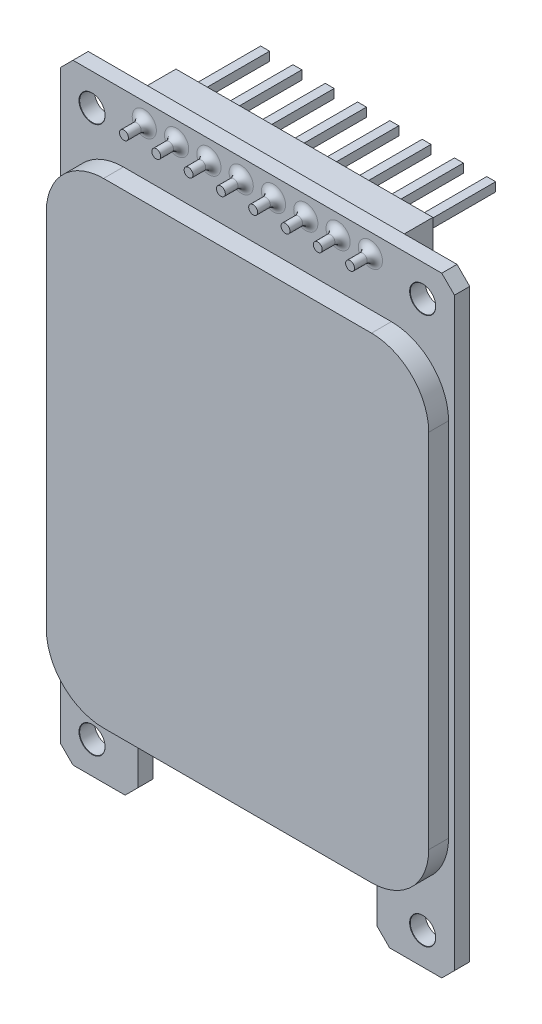
SolidWorks part; units mm, degrees
ref_plane "Ebene vorne" through (0, 0, 0) normal (1, 0, 0) x (0, 1, 0)
ref_plane "Ebene oben" through (0, 0, 0) normal (0, 0, 1) x (0, 1, 0)
ref_plane "Ebene rechts" through (0, 0, 0) normal (0, 1, 0) x (-1, 0, 0)
sketch "Skizze1" plane through (0, 0, 0) normal (0, 0, 1) x (0, 1, 0)
  line L0 (-24, 9.4) -> (-18.5, 9.4)
  line L1 (-24, -15.5) -> (24, -15.5)
  line L2 (-24, -15.5) -> (-24, -9.4)
  line L3 (-24, 15.5) -> (24, 15.5)
  line L4 (24, -15.5) -> (24, 15.5)
  line L5 (-24, -15.5) -> (24, 15.5) construction
  line L6 (-24, 15.5) -> (24, -15.5) construction
  line L7 (-18.5, 9.4) -> (-18.5, -9.4)
  line L8 (-18.5, -9.4) -> (-24, -9.4)
  line L9 (-24, 9.4) -> (-24, 15.5)
  point P0 (0, 0)
  point P8 (-18.5, 0)
  dimension "D1" = 48
  dimension "D2" = 31
  dimension "D3" = 5.5
  dimension "D4" = 6.1
extrude "Aufsatz-Linear austragen1" add sketch "Skizze1" along normal blind 1.2
chamfer "Fase1" distance 1 angle 45 6 edges at (-9.4, -24, 0.6) (9.4, -24, 0.6) (-15.5, -24, 0.6) (-15.5, 24, 0.6) (15.5, -24, 0.6) (15.5, 24, 0.6)
hole_wizard "Ø2.0 (2) Durchmesser Bohrung1" positions "Skizze2" profile "Skizze3" hole size "Ø2.0" standard "DIN" end condition up to next
sketch "Skizze2" plane through (0, 0, 1.2) normal (0, 0, 1) x (0, -1, 0)
  line L7 (-21.5, 13) -> (21.5, 13) construction
  line L8 (-21.5, 13) -> (-21.5, -13) construction
  line L9 (-21.5, -13) -> (21.5, -13) construction
  line L10 (21.5, -13) -> (21.5, 13) construction
  line L12 (-21.5, 0) -> (0, 0) construction
  line L14 (0, 0) -> (0, 13) construction
  point P2 (21.5, 13)
  point P4 (-21.5, 13)
  point P36 (21.5, -13)
  point P38 (-21.5, -13)
  dimension "D1" = 26
  dimension "D2" = 43
sketch "Skizze3" plane through (13, -21.5, 1.2) normal (1, 0, 0) x (0, -1, 0)
  line L0 (0, 0) -> (0, 1.2)
  line L1 (0, 1.2) -> (1, 1.2)
  line L2 (1, 1.2) -> (1, 0.025)
  line L3 (1, 0.025) -> (1.025, 0)
  line L5 (1.025, 0) -> (0, 0)
  line L6 (-1, 0.025) -> (-1.025, 0) construction
  line L11 (0, -6.35) -> (0, 107.95) construction
  dimension "Bohrerdurchmesser" = 2
  dimension "Bohrungstiefe" = 1.2
  dimension "Senkdurchmesser2 (Oben)" = 2.05
  dimension "Senkwinkel2 (Oben)" = 90
sketch "Skizze4" plane through (0, 0, 1.2) normal (0, 0, 1) x (1, 0, 0)
  line L1 (10.535, -18.715) -> (-10.535, -18.715)
  line L2 (15.035, -14.215) -> (15.035, 14.215)
  line L3 (10.535, 18.715) -> (-10.535, 18.715)
  line L4 (-15.035, -14.215) -> (-15.035, 14.215)
  line L5 (13.717, -17.397) -> (-13.717, 17.397) construction
  line L6 (13.717, 17.397) -> (-13.717, -17.397) construction
  arc A0 (-10.535, 18.715) -> (-15.035, 14.215) centre (-10.535, 14.215) ccw
  arc A1 (15.035, 14.215) -> (10.535, 18.715) centre (10.535, 14.215) ccw
  arc A2 (-15.035, -14.215) -> (-10.535, -18.715) centre (-10.535, -14.215) ccw
  arc A3 (10.535, -18.715) -> (15.035, -14.215) centre (10.535, -14.215) ccw
  point P0 (0, 0)
  point P7 (13.717, 17.397)
  point P25 (-13.717, 17.397)
  point P27 (-13.717, -17.397)
  point P29 (13.717, -17.397)
  dimension "D1" = 4.5
  dimension "D2" = 30.07
  dimension "D3" = 37.43
extrude "Aufsatz-Linear austragen2" add sketch "Skizze4" along normal blind 1.56
sketch "Skizze5" plane through (0, 0, 1.2) normal (0, 0, 1) x (1, 0, 0)
  line L0 (-15.5, 23) -> (-15.5, -23) construction
  line L1 (14.5, 24) -> (-14.5, 24) construction
  line L2 (-8.89, 22.5) -> (-6.35, 22.5) construction
  circle A0 centre (-8.89, 22.5) radius 0.35
  circle A1 centre (-6.35, 22.5) radius 0.35
  circle A2 centre (-3.81, 22.5) radius 0.35
  circle A3 centre (-1.27, 22.5) radius 0.35
  circle A4 centre (1.27, 22.5) radius 0.35
  circle A5 centre (3.81, 22.5) radius 0.35
  circle A6 centre (6.35, 22.5) radius 0.35
  circle A7 centre (8.89, 22.5) radius 0.35
  dimension "D1" = 0.7
  dimension "D2" = 6.61
  dimension "D3" = 1.5
  dimension "D5" = 2.54
  dimension "D4" = 8
extrude "Aufsatz-Linear austragen3" add sketch "Skizze5" along normal blind 1.6 and the other way blind 9.7
fillet "Verrundung1" radius 0.6 8 edges at (8.54, 22.5, 1.2) (6, 22.5, 1.2) (3.46, 22.5, 1.2) (0.92, 22.5, 1.2) (-4.16, 22.5, 1.2) (-6.7, 22.5, 1.2) (-9.24, 22.5, 1.2) (-1.62, 22.5, 1.2)
sketch "Skizze6" plane through (0, 0, 0) normal (0, 0, -1) x (1, 0, 0)
  line L0 (0, 0) -> (0, -22.5) construction
  line L1 (10.1, -23.75) -> (-10.1, -23.75)
  line L2 (10.1, -23.75) -> (10.1, -21.25)
  line L3 (10.1, -21.25) -> (-10.1, -21.25)
  line L4 (-10.1, -23.75) -> (-10.1, -21.25)
  line L5 (10.1, -23.75) -> (-10.1, -21.25) construction
  line L6 (10.1, -21.25) -> (-10.1, -23.75) construction
  line L7 (14.5, -24) -> (-14.5, -24) construction
  point P0 (0, -22.5)
  dimension "D1" = 20.2
  dimension "D2" = 2.5
  dimension "D3" = 1.5
extrude "Aufsatz-Linear austragen4" add sketch "Skizze6" along normal blind 2.5
sketch "Skizze7" plane through (0, 0, -2.5) normal (0, 0, -1) x (1, 0, 0)
  line L0 (6, -22.85) -> (6.7, -22.85)
  line L1 (8.54, -22.85) -> (9.24, -22.85)
  line L2 (8.54, -22.85) -> (8.54, -22.15)
  line L3 (8.54, -22.15) -> (9.24, -22.15)
  line L4 (9.24, -22.85) -> (9.24, -22.15)
  line L5 (8.54, -22.85) -> (9.24, -22.15) construction
  line L6 (8.54, -22.15) -> (9.24, -22.85) construction
  line L7 (6, -22.85) -> (6, -22.15)
  line L8 (6, -22.15) -> (6.7, -22.15)
  line L9 (6.7, -22.85) -> (6.7, -22.15)
  line L10 (6, -22.85) -> (6.7, -22.15) construction
  line L11 (6, -22.15) -> (6.7, -22.85) construction
  line L12 (3.46, -22.85) -> (4.16, -22.85)
  line L13 (3.46, -22.85) -> (3.46, -22.15)
  line L14 (3.46, -22.15) -> (4.16, -22.15)
  line L15 (4.16, -22.85) -> (4.16, -22.15)
  line L16 (3.46, -22.85) -> (4.16, -22.15) construction
  line L17 (3.46, -22.15) -> (4.16, -22.85) construction
  line L18 (0.92, -22.85) -> (1.62, -22.85)
  line L19 (0.92, -22.85) -> (0.92, -22.15)
  line L20 (0.92, -22.15) -> (1.62, -22.15)
  line L21 (1.62, -22.85) -> (1.62, -22.15)
  line L22 (0.92, -22.85) -> (1.62, -22.15) construction
  line L23 (0.92, -22.15) -> (1.62, -22.85) construction
  line L24 (-1.62, -22.85) -> (-0.92, -22.85)
  line L25 (-1.62, -22.85) -> (-1.62, -22.15)
  line L26 (-1.62, -22.15) -> (-0.92, -22.15)
  line L27 (-0.92, -22.85) -> (-0.92, -22.15)
  line L28 (-1.62, -22.85) -> (-0.92, -22.15) construction
  line L29 (-1.62, -22.15) -> (-0.92, -22.85) construction
  line L30 (-4.16, -22.85) -> (-3.46, -22.85)
  line L31 (-4.16, -22.85) -> (-4.16, -22.15)
  line L32 (-4.16, -22.15) -> (-3.46, -22.15)
  line L33 (-3.46, -22.85) -> (-3.46, -22.15)
  line L34 (-4.16, -22.85) -> (-3.46, -22.15) construction
  line L35 (-4.16, -22.15) -> (-3.46, -22.85) construction
  line L36 (-6.7, -22.85) -> (-6, -22.85)
  line L37 (-6.7, -22.85) -> (-6.7, -22.15)
  line L38 (-6.7, -22.15) -> (-6, -22.15)
  line L39 (-6, -22.85) -> (-6, -22.15)
  line L40 (-6.7, -22.85) -> (-6, -22.15) construction
  line L41 (-6.7, -22.15) -> (-6, -22.85) construction
  line L42 (-9.24, -22.85) -> (-8.54, -22.85)
  line L43 (-9.24, -22.85) -> (-9.24, -22.15)
  line L44 (-9.24, -22.15) -> (-8.54, -22.15)
  line L45 (-8.54, -22.85) -> (-8.54, -22.15)
  line L46 (-9.24, -22.85) -> (-8.54, -22.15) construction
  line L47 (-9.24, -22.15) -> (-8.54, -22.85) construction
  line L48 (8.89, -22.5) -> (6.35, -22.5) construction
  circle A0 centre (8.89, -22.5) radius 0.35 construction
  point P0 (8.89, -22.5)
  point P10 (6.35, -22.5)
  point P15 (3.81, -22.5)
  point P20 (1.27, -22.5)
  point P25 (-1.27, -22.5)
  point P30 (-3.81, -22.5)
  point P35 (-6.35, -22.5)
  point P40 (-8.89, -22.5)
  dimension "D2" = 2.54
  dimension "D1" = 8
extrude "Aufsatz-Linear austragen5" add sketch "Skizze7" along normal up to surface (6 mm away) up to face at (-8.54, 22.5, -8.5)
chamfer "Fase2" distance 0.2 angle 45 32 edges at (8.54, 22.5, -8.5) (8.89, 22.15, -8.5) (9.24, 22.5, -8.5) (8.89, 22.85, -8.5) (6, 22.5, -8.5) (6.35, 22.15, -8.5) (6.7, 22.5, -8.5) (6.35, 22.85, -8.5) (3.46, 22.5, -8.5) (3.81, 22.15, -8.5) (4.16, 22.5, -8.5) (3.81, 22.85, -8.5) (0.92, 22.5, -8.5) (1.27, 22.15, -8.5) (1.62, 22.5, -8.5) (1.27, 22.85, -8.5) (-1.62, 22.5, -8.5) (-1.27, 22.15, -8.5) (-0.92, 22.5, -8.5) (-1.27, 22.85, -8.5) (-4.16, 22.5, -8.5) (-3.81, 22.15, -8.5) (-3.46, 22.5, -8.5) (-3.81, 22.85, -8.5) (-6.7, 22.5, -8.5) (-6.35, 22.15, -8.5) (-6, 22.5, -8.5) (-6.35, 22.85, -8.5) (-9.24, 22.5, -8.5) (-8.89, 22.15, -8.5) (-8.54, 22.5, -8.5) (-8.89, 22.85, -8.5)
